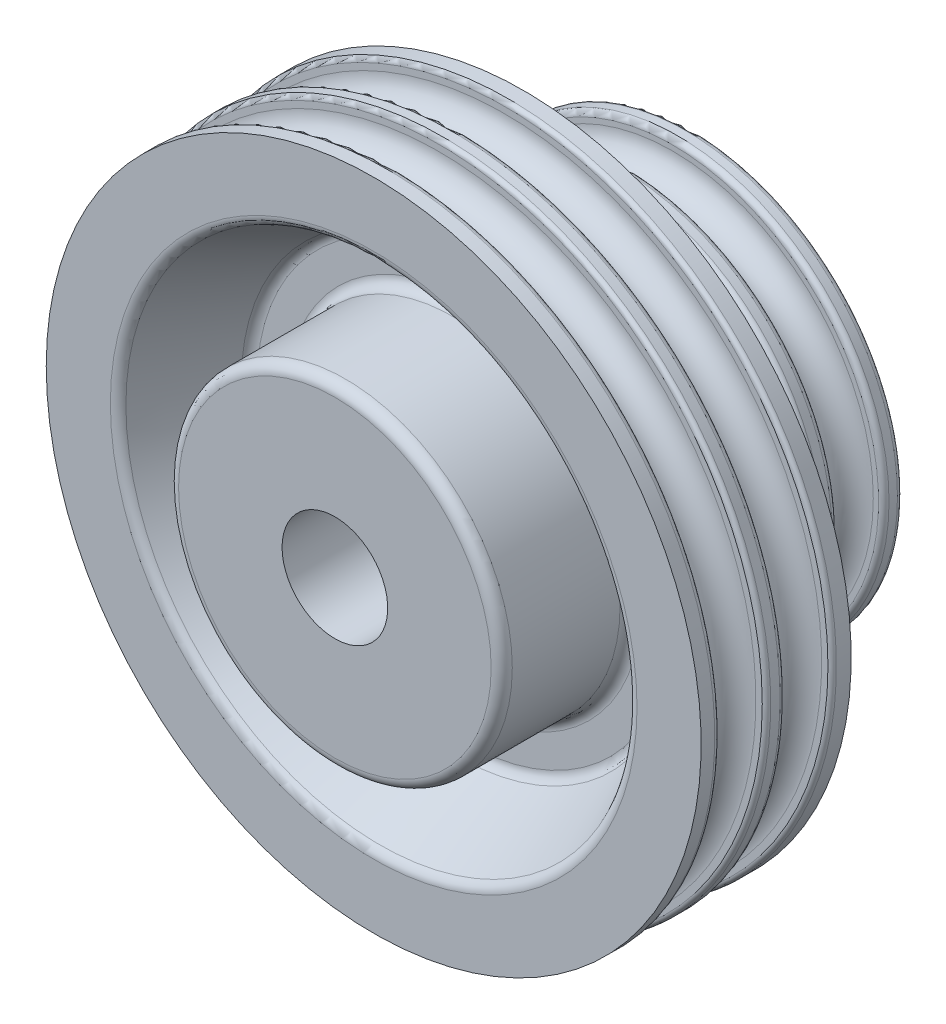
SolidWorks part; units mm, degrees
ref_plane "Front Plane" through (0, 0, 0) normal (0, 0, 1) x (1, 0, 0)
ref_plane "Top Plane" through (0, 0, 0) normal (0, 1, 0) x (1, 0, 0)
ref_plane "Right Plane" through (0, 0, 0) normal (1, 0, 0) x (0, 0, -1)
sketch "Sketch1" plane through (0, 0, 0) normal (0, 1, 0) x (1, 0, 0)
  line L0 (-69.2513, 55.2783) -> (-69.2513, -14.7217) construction
  line L1 (-38.2513, -2.9504) -> (-44.3218, -2.9504)
  line L2 (-38.6513, 3.2347) -> (-39.2513, 3.2347)
  line L3 (-38.2513, 4.5162) -> (-38.2513, 3.6347)
  line L4 (-39.2513, -1.1653) -> (-38.6513, -1.1653)
  line L5 (-50.3351, 19.1457) -> (-49.7513, 19.1457)
  line L6 (-58.2513, 27.1438) -> (-58.2513, 21.1438)
  line L7 (-38.2513, -1.6645) -> (-38.2513, -2.896)
  line L8 (-59.2513, -0.6253) -> (-59.2513, 21.1438)
  line L9 (-53.4551, -5.6253) -> (-53.4551, 4.5803)
  line L10 (-45.0898, 11.2531) -> (-38.2513, 11.2531)
  line L11 (-49.2513, 25.8358) -> (-49.2513, 26.6355)
  line L12 (-39.2513, 5.0162) -> (-38.7513, 5.0162)
  line L13 (-49.7512, 27.1438) -> (-58.2513, 27.1438)
  line L14 (-52.4551, 5.5803) -> (-49.6584, 5.5803)
  line L15 (-50.2513, 20.9438) -> (-49.7513, 20.9438)
  line L16 (-49.2513, 19.6457) -> (-49.2513, 20.4438)
  line L17 (-49.7512, 25.3438) -> (-50.2513, 25.3438)
  line L18 (-38.6513, 9.4531) -> (-39.2513, 9.4531)
  line L19 (-38.2513, 11.2531) -> (-38.2513, 9.8531)
  line L20 (-58.2513, -0.6253) -> (-59.2513, -0.6253)
  line L21 (-48.7561, 5.0114) -> (-45.2241, -2.3815)
  line L22 (-45.7903, 11.2531) -> (-45.0898, 11.2531)
  line L23 (-54.4551, -6.6253) -> (-58.2513, -6.6253)
  line L25 (-59.2513, 21.1438) -> (-58.2513, 21.1438)
  line L26 (-58.2513, -0.6253) -> (-58.2513, -6.6253)
  line L27 (-50.5903, 14.7531) -> (-49.7513, 14.7531)
  line L28 (-49.2513, 14.2531) -> (-49.2513, 11.8634)
  line L29 (-49.2513, 11.8634) -> (-49.2513, 11.7531)
  line L30 (-48.7513, 11.2531) -> (-45.7903, 11.2531)
  line L31 (-38.2513, -2.9504) -> (-38.2513, -2.896)
  arc A0 (-38.2513, 3.6347) -> (-38.6513, 3.2347) centre (-38.6513, 3.6347) cw
  arc A1 (-38.2513, -1.6645) -> (-38.6513, -1.1653) centre (-38.7512, -1.6553) ccw
  arc A2 (-50.3351, 19.1457) -> (-50.5903, 14.7531) centre (-50.4627, 16.9494) ccw
  arc A3 (-50.2513, 25.3438) -> (-50.2513, 20.9438) centre (-50.2513, 23.1438) ccw
  arc A4 (-49.2513, 26.6355) -> (-49.7512, 27.1438) centre (-49.7512, 26.6438) ccw
  arc A5 (-49.7513, 19.1457) -> (-49.2513, 19.6457) centre (-49.7513, 19.6457) ccw
  arc A6 (-49.7513, 20.9438) -> (-49.2513, 20.4438) centre (-49.7513, 20.4438) cw
  arc A7 (-49.2513, 25.8358) -> (-49.7512, 25.3438) centre (-49.7512, 25.8438) cw
  arc A8 (-38.7513, 5.0162) -> (-38.2513, 4.5162) centre (-38.7513, 4.5162) cw
  arc A9 (-39.2513, 3.2347) -> (-39.2513, -1.1653) centre (-39.2513, 1.0347) ccw
  arc A10 (-49.6584, 5.5803) -> (-48.7561, 5.0114) centre (-49.6584, 4.5803) cw
  arc A11 (-38.2513, 9.8531) -> (-38.6513, 9.4531) centre (-38.6513, 9.8531) cw
  arc A12 (-53.4551, 4.5803) -> (-52.4551, 5.5803) centre (-52.4551, 4.5803) cw
  arc A13 (-39.2513, 9.4531) -> (-39.2513, 5.0162) centre (-39.2513, 7.2347) ccw
  arc A14 (-45.2241, -2.3815) -> (-44.3218, -2.9504) centre (-44.3218, -1.9504) ccw
  arc A15 (-49.7513, 14.7531) -> (-49.2513, 14.2531) centre (-49.7513, 14.2531) cw
  arc A16 (-53.4551, -5.6253) -> (-54.4551, -6.6253) centre (-54.4551, -5.6253) cw
  arc A17 (-49.2513, 11.7531) -> (-48.7513, 11.2531) centre (-48.7513, 11.7531) ccw
  point P66 (-53.4643, -2.9163)
  dimension "D11" = 4.4
  dimension "D12" = 4.4
  dimension "D4" = 0.5
  dimension "D8" = 6
  dimension "D15" = 30
  dimension "D17" = 1.8
  dimension "D18" = 1.2315
  dimension "D26" = 1
  dimension "D27" = 0.5
  dimension "D28" = 0.5
  dimension "D29" = 33.7691
  dimension "D24" = 0.5
  dimension "D25" = 1
  dimension "D3" = 11
  dimension "D5" = 19
  dimension "D6" = 3.5
  dimension "D7" = 0.6
  dimension "D9" = 0.6
  dimension "D13" = 1.8
  dimension "D14" = 6
  dimension "D16" = 1
  dimension "D19" = 1
  dimension "D20" = 1
  dimension "D21" = 1
  dimension "D22" = 1
  dimension "D23" = 1
  dimension "D30" = 31
revolve "Revolve1" add sketch "Sketch1" angle 360 about L0
sketch "Sketch2" plane through (0, 0, 6.6253) normal (0, 0, 1) x (1, 0, 0)
  circle A0 centre (-69.2513, 0) radius 11
extrude "Boss-Extrude1" add sketch "Sketch2" against normal blind 34
sketch "Sketch3" plane through (0, 0, -27.3747) normal (0, 0, -1) x (-1, 0, 0)
  circle A0 centre (69.2513, 0) radius 5
extrude "Cut-Extrude1" cut sketch "Sketch3" against normal blind 43
